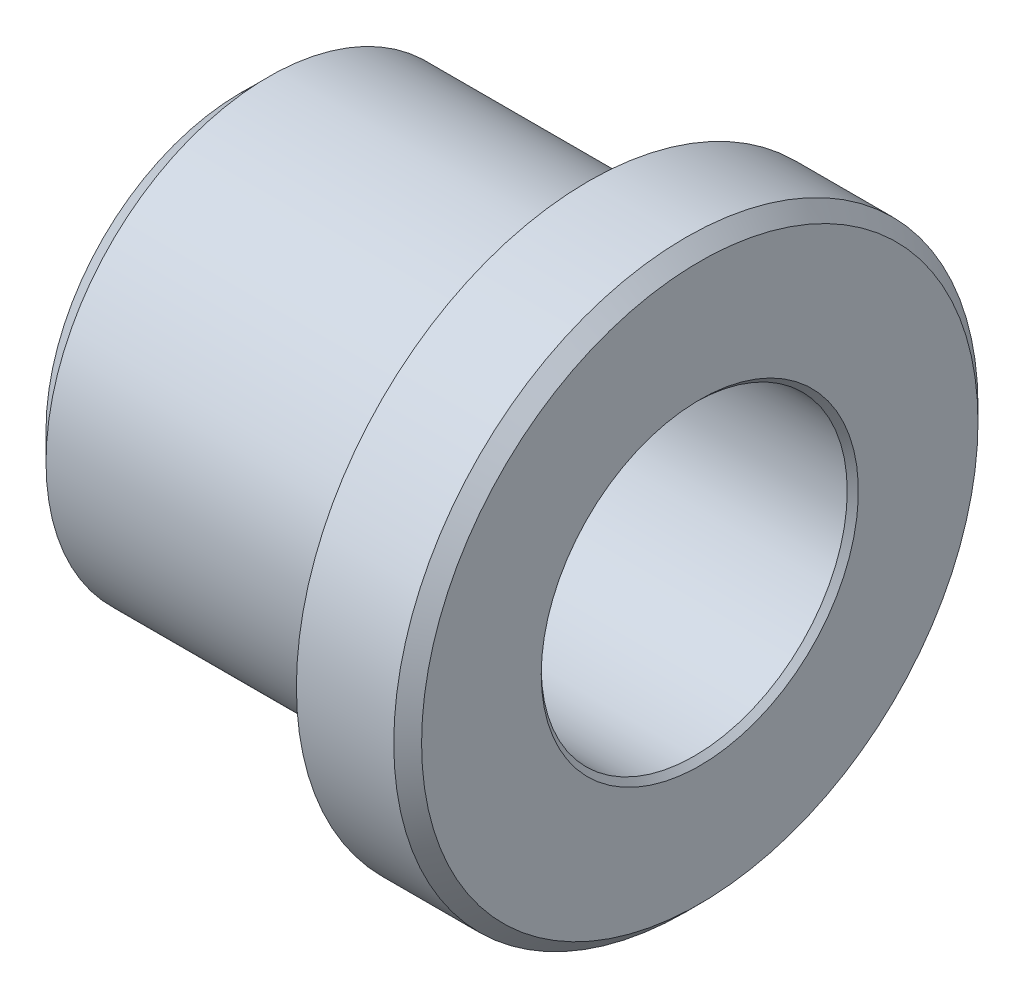
SolidWorks part; units mm, degrees
ref_plane "Plan1" through (0, 0, 0) normal (0, 0, 1) x (1, 0, 0)
ref_plane "Plan2" through (0, 0, 0) normal (0, 1, 0) x (1, 0, 0)
ref_plane "Plan3" through (0, 0, 0) normal (1, 0, 0) x (0, 0, -1)
sketch "Esquisse1" plane through (0, 0, 0) normal (0, 0, 1) x (1, 0, 0)
  line L0 (11.3908, 0) -> (106.0223, 0) construction
  line L1 (12.5, 10.5) -> (16.5, 10.5)
  line L2 (12.5, 10.5) -> (12.5, 8)
  line L3 (0, 5.5) -> (16.5, 5.5)
  line L4 (16.5, 10.5) -> (16.5, 5.5)
  line L5 (12.5, 8) -> (0, 8)
  line L8 (0, 8) -> (0, 5.5)
  dimension "D1" = 5.5
  dimension "D2" = 10.5
  dimension "D3" = 8
  dimension "D4" = 4
  dimension "D5" = 12.5
revolve "Base-Révolution" add sketch "Esquisse1" angle 360 about L0
chamfer "Chanfrein1" distance 0.5 angle 45
chamfer "Chanfrein2" distance 1 angle 45
chamfer "Chanfrein3" distance 0.2 angle 45
